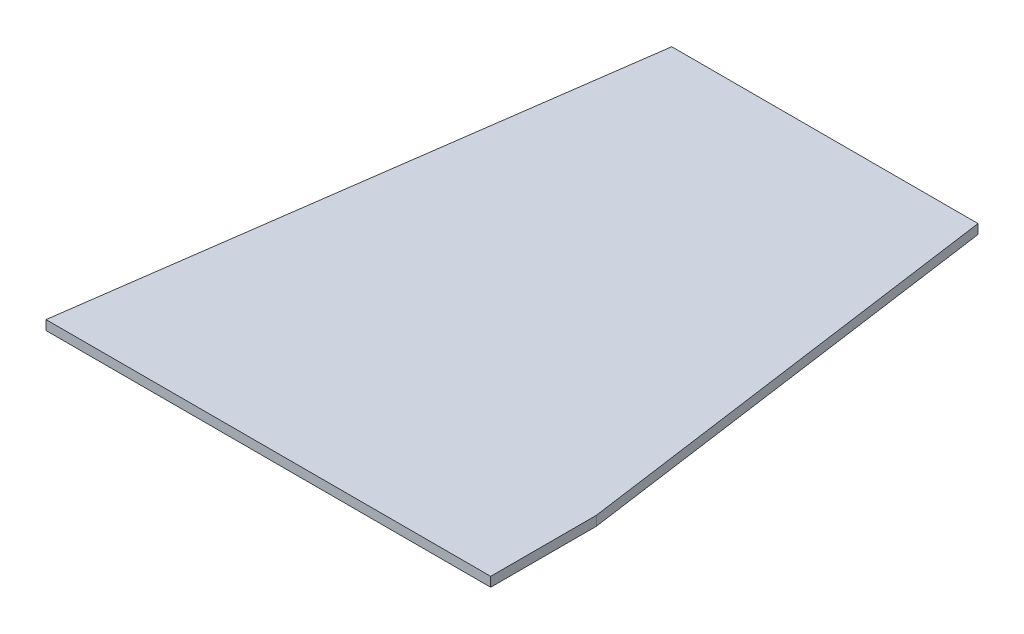
SolidWorks part; units mm, degrees
ref_plane "前视基准面" through (0, 0, 0) normal (0, 0, 1) x (1, 0, 0)
ref_plane "上视基准面" through (0, 0, 0) normal (0, 1, 0) x (1, 0, 0)
ref_plane "右视基准面" through (0, 0, 0) normal (1, 0, 0) x (0, 0, -1)
sketch "草图1" plane through (0, 0, 0) normal (0, 1, 0) x (1, 0, 0)
  line L0 (0, 0) -> (14.5, 104)
  line L1 (14.5, 104) -> (72.5, 104)
  line L2 (72.5, 104) -> (87, 0)
  line L3 (87, 0) -> (0, 0)
  line L4 (43.5, 0) -> (43.5, 104) construction
  dimension "D1" = 58
  dimension "D2" = 104
  dimension "D3" = 87
extrude "凸台-拉伸1" add sketch "草图1" along normal blind 1.8
sketch "草图2" plane through (0, 1.8, 0) normal (0, 1, 0) x (1, 0, 0)
  line L0 (87, 0) -> (72.5, 104) construction
  line L1 (84.2115, 20) -> (87, 20)
  line L2 (84.2115, 20) -> (84.2115, 0)
  line L3 (84.2115, 0) -> (87, 0)
  line L4 (87, 20) -> (87, 0)
  dimension "D1" = 20
extrude "切除-拉伸1" cut sketch "草图2" against normal through all
